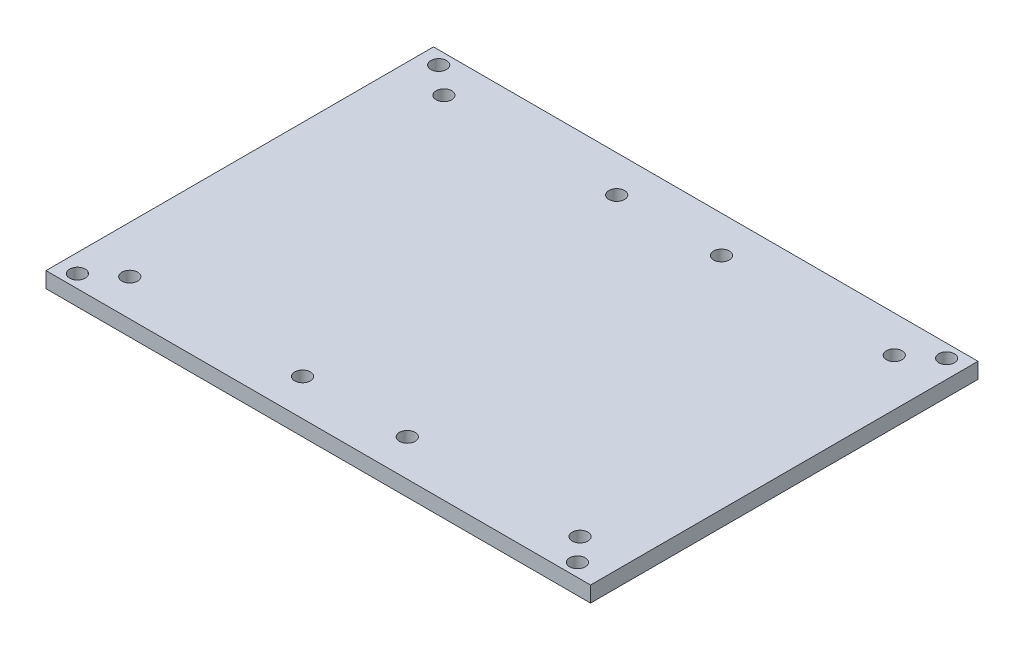
SolidWorks part; units mm, degrees
ref_plane "前视基准面" through (0, 0, 0) normal (0, 0, 1) x (1, 0, 0)
ref_plane "上视基准面" through (0, 0, 0) normal (0, 1, 0) x (1, 0, 0)
ref_plane "右视基准面" through (0, 0, 0) normal (1, 0, 0) x (0, 0, -1)
sketch "草图1" plane through (0, 0, 0) normal (0, 1, 0) x (1, 0, 0)
  line L1 (-52, 37) -> (52, 37)
  line L2 (-52, 37) -> (-52, -37)
  line L3 (-52, -37) -> (52, -37)
  line L4 (52, 37) -> (52, -37)
  line L5 (-52, 37) -> (52, -37) construction
  line L6 (-52, -37) -> (52, 37) construction
  point P0 (0, 0)
  point P6 (0, 0)
extrude "稳压模块底座" add sketch "草图1" along normal blind 3
sketch "草图2" plane through (0, 3, 0) normal (0, 1, 0) x (1, 0, 0)
  circle A0 centre (-43, 30) radius 1.5
  circle A1 centre (-43, -30) radius 1.5
  circle A2 centre (-10, 30) radius 1.5
  circle A3 centre (-10, -30) radius 1.5
  circle A4 centre (10, 30) radius 1.5
  circle A5 centre (10, -30) radius 1.5
  circle A6 centre (43, 30) radius 1.5
  circle A7 centre (43, -30) radius 1.5
  circle A8 centre (48.5, 34.5) radius 1.5
  circle A9 centre (-48.5, 34.5) radius 1.5
  circle A10 centre (-48.5, -34.5) radius 1.5
  circle A11 centre (47, -34.5) radius 1.5
extrude "固定位孔" cut sketch "草图2" against normal through all
